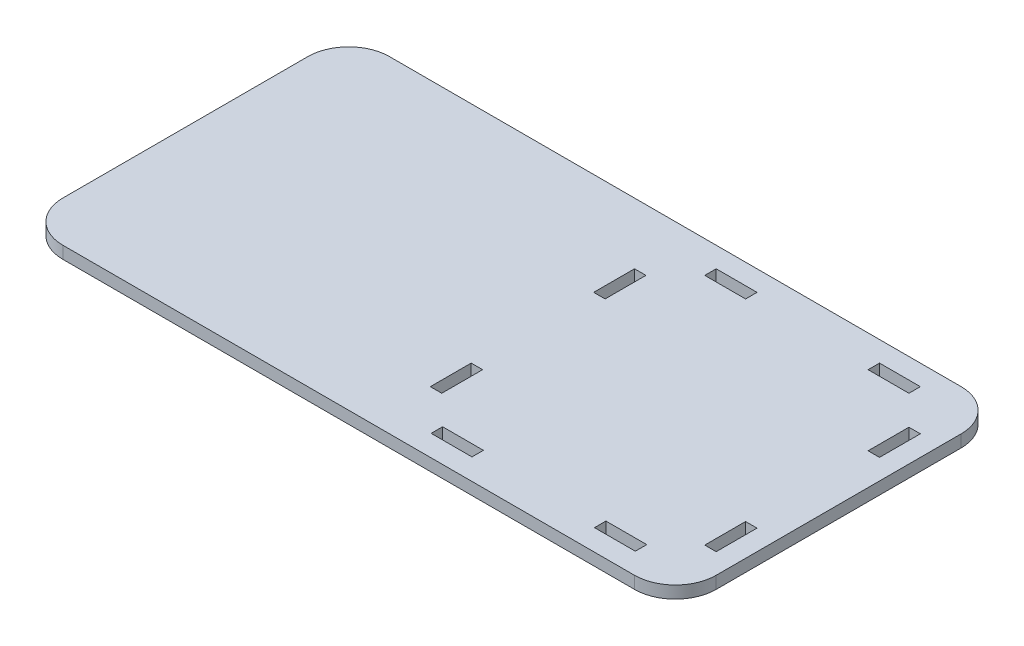
SolidWorks part; units mm, degrees
ref_plane "Plan de face" through (0, 0, 0) normal (0, 0, 1) x (1, 0, 0)
ref_plane "Plan de dessus" through (0, 0, 0) normal (0, 1, 0) x (1, 0, 0)
ref_plane "Plan de droite" through (0, 0, 0) normal (1, 0, 0) x (0, 0, -1)
sketch "Esquisse2" plane through (0, 0, 0) normal (0, 1, 0) x (1, 0, 0)
  line L1 (10, 0) -> (150, 0)
  line L2 (0, 10) -> (0, 70)
  line L3 (10, 80) -> (150, 80)
  line L4 (160, 10) -> (160, 70)
  arc A0 (150, 80) -> (160, 70) centre (150, 70) cw
  arc A1 (150, 0) -> (160, 10) centre (150, 10) ccw
  arc A2 (10, 0) -> (0, 10) centre (10, 10) cw
  arc A3 (0, 70) -> (10, 80) centre (10, 70) cw
  point P7 (160, 80)
  point P12 (0, 0)
  point P15 (0, 80)
  dimension "D3" = 10
  dimension "D1" = 160
  dimension "D2" = 80
extrude "Boss.-Extru.1" add sketch "Esquisse2" along normal blind 3
sketch "Esquisse4" plane through (0, 3, 0) normal (0, 1, 0) x (1, 0, 0)
  line L0 (150, 80) -> (10, 80) construction
  line L1 (145, 75) -> (135, 75)
  line L2 (145, 75) -> (145, 72.2)
  line L3 (145, 72.2) -> (135, 72.2)
  line L4 (135, 75) -> (135, 72.2)
  line L5 (160, 10) -> (160, 70) construction
  line L6 (105, 75) -> (105, 72.2)
  line L7 (105, 75) -> (95, 75)
  line L8 (95, 75) -> (95, 72.2)
  line L9 (105, 72.2) -> (95, 72.2)
  line L10 (105, 8) -> (105, 5.2)
  line L11 (105, 8) -> (95, 8)
  line L12 (95, 8) -> (95, 5.2)
  line L13 (105, 5.2) -> (95, 5.2)
  line L14 (145, 8) -> (145, 5.2)
  line L15 (145, 8) -> (135, 8)
  line L16 (135, 8) -> (135, 5.2)
  line L17 (145, 5.2) -> (135, 5.2)
  line L18 (160, 10) -> (160, 70) construction
  dimension "D1" = 5
  dimension "D2" = 2.8
  dimension "D3" = 10
  dimension "D4" = 15
  dimension "D7" = 65
  dimension "D5" = 2
  dimension "D6" = 2
extrude "Enlèv. mat.-Extru.2" cut sketch "Esquisse4" against normal through all
sketch "Esquisse5" plane through (0, 3, 0) normal (0, 1, 0) x (1, 0, 0)
  line L0 (160, 10) -> (160, 70) construction
  line L1 (155, 65) -> (152.2, 65)
  line L2 (155, 65) -> (155, 55)
  line L3 (155, 55) -> (152.2, 55)
  line L4 (152.2, 65) -> (152.2, 55)
  line L5 (85, 65) -> (87.8, 65)
  line L6 (85, 65) -> (85, 55)
  line L7 (85, 55) -> (87.8, 55)
  line L8 (87.8, 65) -> (87.8, 55)
  line L12 (85, 25) -> (85, 15)
  line L13 (85, 25) -> (87.8, 25)
  line L14 (87.8, 25) -> (87.8, 15)
  line L15 (85, 15) -> (87.8, 15)
  line L16 (155, 25) -> (155, 15)
  line L17 (155, 25) -> (152.2, 25)
  line L18 (152.2, 25) -> (152.2, 15)
  line L19 (155, 15) -> (152.2, 15)
  line L21 (160, 10) -> (160, 70) construction
  line L22 (150, 80) -> (10, 80) construction
  line L23 (10, 0) -> (150, 0) construction
  dimension "D1" = 5
  dimension "D2" = 10
  dimension "D3" = 2.8
  dimension "D5" = 10
  dimension "D6" = 2.8
  dimension "D7" = 75
  dimension "D8" = 15
  dimension "D10" = 15
  dimension "D11" = 15
  dimension "D12" = 15
  dimension "D9" = 2
extrude "Enlèv. mat.-Extru.3" cut sketch "Esquisse5" against normal through all
